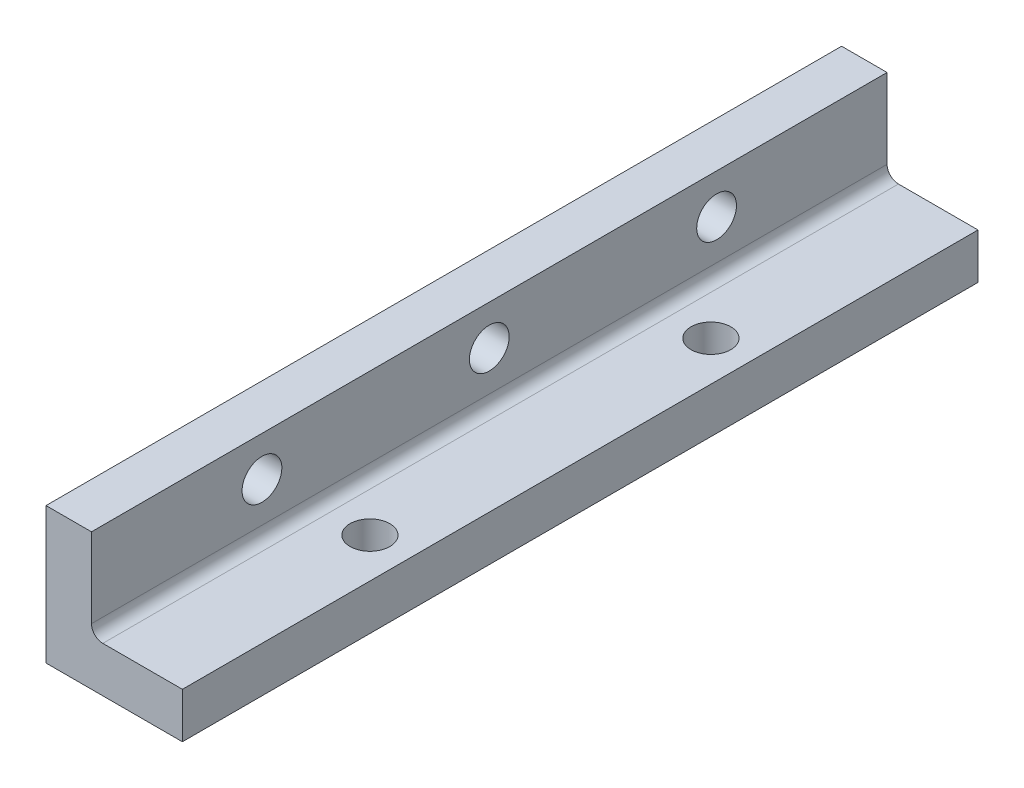
SolidWorks part; units mm, degrees
ref_plane "Ön Düzlem" through (0, 0, 0) normal (0, 0, 1) x (1, 0, 0)
ref_plane "Üst Düzlem" through (0, 0, 0) normal (0, 1, 0) x (1, 0, 0)
ref_plane "Sağ Düzlem" through (0, 0, 0) normal (1, 0, 0) x (0, 0, -1)
sketch "Sketch1" plane through (0, 0, 0) normal (0, 0, 1) x (1, 0, 0)
  line L1 (-7.272, 5.4559) -> (-3.272, 5.4559)
  line L2 (-7.272, 5.4559) -> (-7.272, -6.5441)
  line L3 (-7.272, -6.5441) -> (-3.272, -6.5441)
  line L4 (-3.272, 5.4559) -> (-3.272, -6.5441)
  line L5 (-7.272, -6.5441) -> (4.728, -6.5441)
  line L6 (-7.272, -6.5441) -> (-7.272, -2.5441)
  line L7 (-7.272, -2.5441) -> (4.728, -2.5441)
  line L8 (4.728, -6.5441) -> (4.728, -2.5441)
  dimension "D1" = 12
  dimension "D2" = 4
  dimension "D3" = 4
  dimension "D4" = 12
extrude "Boss-Extrude1" add sketch "Sketch1" along normal blind 70 contours L2 L7 L4 L1 | L7 L2 L3 L4 | L5 L8 L7 L4
fillet "Fillet1" radius 1 1 edges at (-3.272, -2.5441, 35)
sketch "Sketch2" plane through (0, -2.5441, 0) normal (0, 1, 0) x (1, 0, 0)
  line L0 (1.228, -35) -> (1.228, -20)
  line L2 (1.228, -35) -> (1.228, -50)
  circle A0 centre (1.228, -50) radius 1.75
  circle A1 centre (1.228, -20) radius 1.75
  dimension "D3" = 3.5
  dimension "D4" = 3.5
  dimension "D2" = 15
  dimension "D1" = 15
sketch "Sketch3" plane through (-3.272, 0, 0) normal (1, 0, 0) x (0, 0, -1)
  circle A0 centre (-35, 1.9559) radius 1.75
  circle A1 centre (-15, 1.9559) radius 1.75
  circle A2 centre (-35, 1.9559) radius 1.75
  circle A3 centre (-55, 1.9559) radius 1.75
  dimension "D1" = 3.5
  dimension "D2" = 2
  dimension "D3" = 2
extrude "Cut-Extrude2" cut sketch "Sketch3" against normal blind 70 contours A3 | A1 | A0
extrude "Cut-Extrude3" cut sketch "Sketch2" against normal up to next contours A1 | A0
